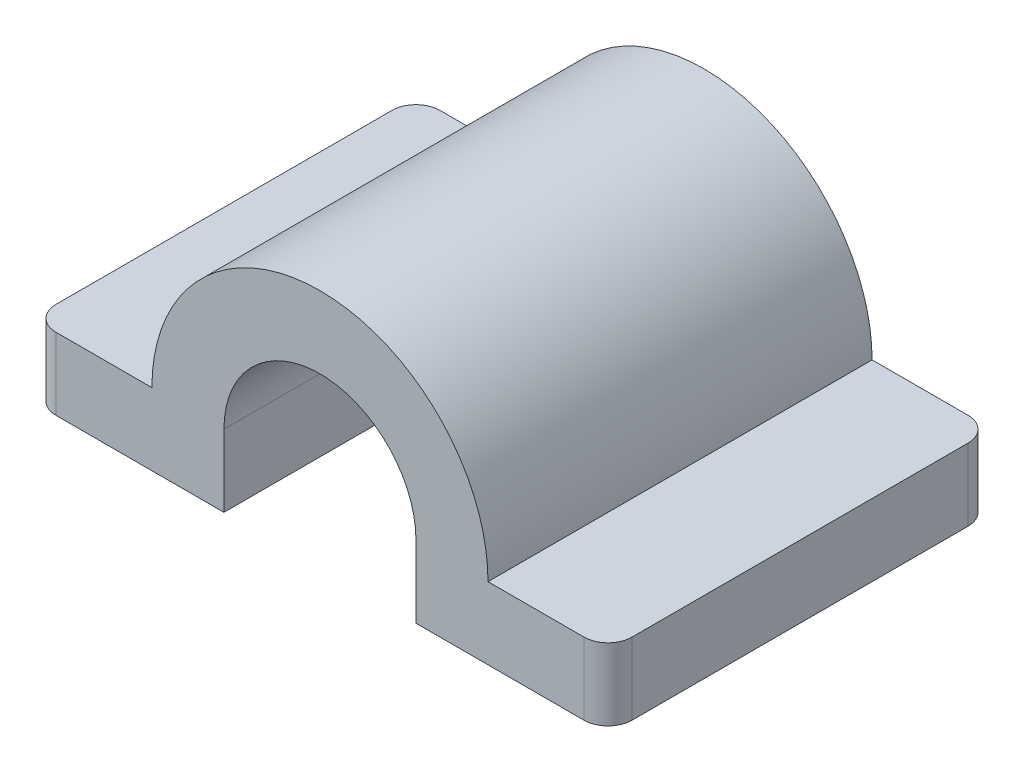
SolidWorks part; units mm, degrees
ref_plane "Спереди" through (0, 0, 0) normal (0, 0, 1) x (1, 0, 0)
ref_plane "Сверху" through (0, 0, 0) normal (0, 1, 0) x (1, 0, 0)
ref_plane "Справа" through (0, 0, 0) normal (1, 0, 0) x (0, 0, -1)
sketch "Эскиз1" plane through (0, 0, 0) normal (0, 0, 1) x (1, 0, 0)
  line L0 (-60, 0) -> (-20, 0)
  line L1 (-20, 0) -> (-20, 15)
  line L2 (20, 15) -> (20, 0)
  line L3 (20, 0) -> (60, 0)
  line L4 (-60, 15) -> (-35, 15)
  line L5 (-35, 15) -> (-35, 15)
  line L6 (35, 15) -> (35, 15)
  line L7 (35, 15) -> (60, 15)
  line L8 (60, 15) -> (60, 0)
  line L9 (-60, 15) -> (-60, 0)
  arc A0 (-20, 15) -> (20, 15) centre (0, 15) cw
  arc A1 (-35, 15) -> (35, 15) centre (0, 15) cw
  dimension "D2" = 20
  dimension "D3" = 120
  dimension "D4" = 50
  dimension "D1" = 15
extrude "Бобышка-Вытянуть1" add sketch "Эскиз1" against normal blind 80
fillet "Скругление1" radius 5 4 edges at (60, 7.5, 0) (60, 7.5, -80) (-60, 7.5, -80) (-60, 7.5, 0)
